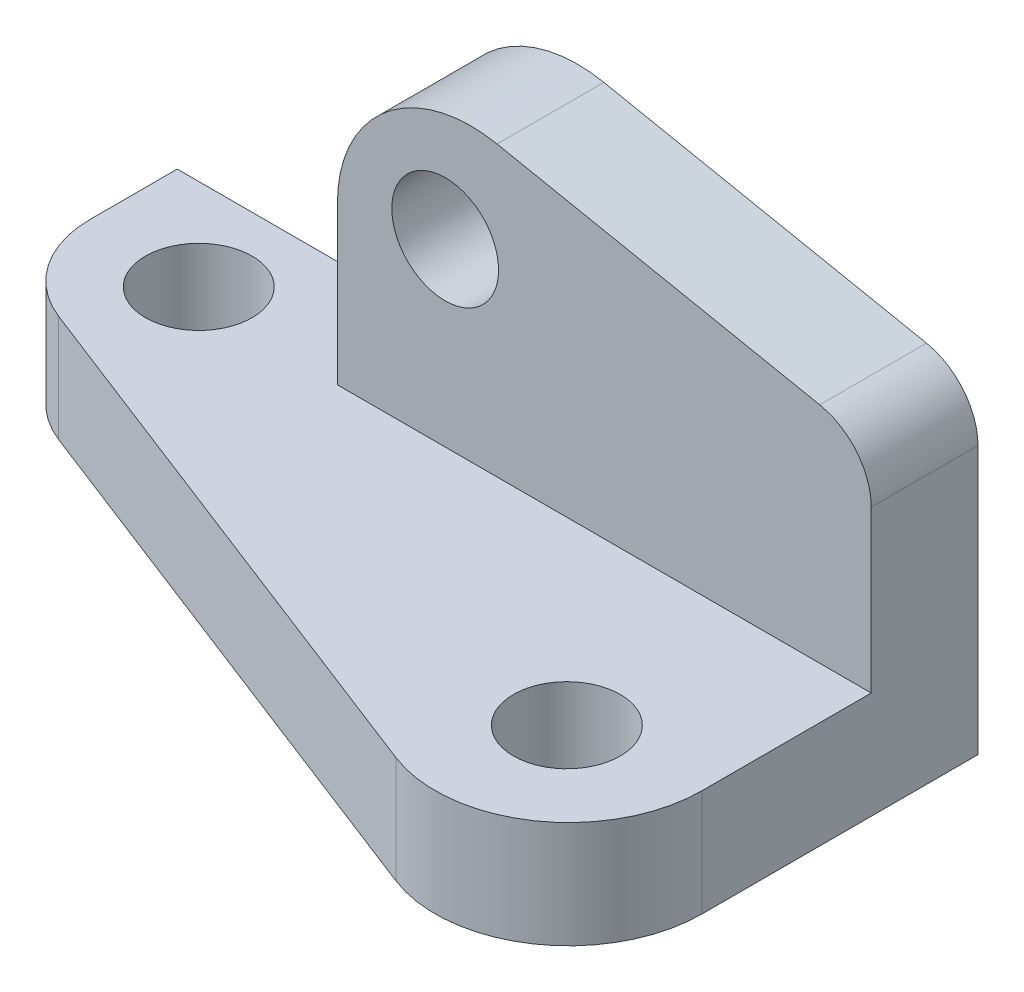
SolidWorks part; units mm, degrees
ref_plane "Front Plane" through (0, 0, 0) normal (0, 0, 1) x (1, 0, 0)
ref_plane "Top Plane" through (0, 0, 0) normal (0, 1, 0) x (1, 0, 0)
ref_plane "Right Plane" through (0, 0, 0) normal (1, 0, 0) x (0, 0, -1)
sketch "Sketch1" plane through (0, 0, 0) normal (0, 1, 0) x (1, 0, 0)
  line L0 (0, 0) -> (150, 0)
  line L1 (0, 0) -> (0, -16.3519)
  line L2 (150, 0) -> (150, -51.6899)
  line L3 (115.9645, -75) -> (12.7716, -35)
  arc A0 (0, -16.3519) -> (12.7716, -35) centre (20, -16.3519) ccw
  arc A1 (150, -51.6899) -> (115.9645, -75) centre (125, -51.6899) cw
  dimension "D1" = 20
  dimension "D2" = 25
  dimension "D3" = 35
  dimension "D4" = 75
  dimension "D5" = 150
extrude "Boss-Extrude1" add sketch "Sketch1" along normal blind 20
sketch "Sketch3" plane through (0, 0, 0) normal (0, 0, 1) x (1, 0, 0)
  line L0 (150, 0) -> (50, 0)
  line L1 (150, 0) -> (0, 0) construction
  line L3 (150, 60) -> (50, 80)
  line L6 (50, 0) -> (50, 80)
  line L7 (150, 0) -> (150, 60)
  dimension "D1" = 60
  dimension "D2" = 100
  dimension "D3" = 80
extrude "Boss-Extrude4" add sketch "Sketch3" along normal blind 20
fillet "Fillet1" radius 25 1 edges at (50, 80, 10)
fillet "Fillet2" radius 12 1 edges at (150, 60, 10)
hole_wizard "Ø20.0mm Dowel Hole2" positions "Sketch10" profile "Sketch11" hole size "Ø20.0" standard "ANSI Metric" end condition through all
sketch "Sketch10" plane through (0, 0, 20) normal (0, 0, 1) x (1, 0, 0)
  point P0 (70.1852, 53.7137)
  point P2 (70.1852, 53.7137)
sketch "Sketch11" plane through (70.1852, 53.7137, 20) normal (1, 0, 0) x (0, -1, 0)
  line L0 (0, 0) -> (0, 20)
  line L1 (0, 20) -> (10, 20)
  line L2 (10, 20) -> (10, 0)
  line L5 (10, 0) -> (0, 0)
  line L11 (0, -6.35) -> (0, 107.95) construction
  dimension "Thru Hole Dia." = 20
  dimension "Thru Hole Depth" = 20
hole_wizard "Ø20.0mm Dowel Hole4" positions "Sketch14" profile "Sketch15" hole size "Ø20.0" standard "ANSI Metric" end condition through all
sketch "Sketch14" plane through (0, 20, 0) normal (0, 1, 0) x (1, 0, 0)
  point P0 (21.1263, -17.1033)
sketch "Sketch15" plane through (21.1263, 20, 17.1033) normal (1, 0, 0) x (0, 0, 1)
  line L0 (0, 0) -> (0, 20)
  line L1 (0, 20) -> (10, 20)
  line L2 (10, 20) -> (10, 0)
  line L5 (10, 0) -> (0, 0)
  line L11 (0, -6.35) -> (0, 107.95) construction
  dimension "Thru Hole Dia." = 20
  dimension "Thru Hole Depth" = 20
hole_wizard "Ø20.0mm Dowel Hole5" positions "Sketch18" profile "Sketch19" hole size "Ø20.0" standard "ANSI Metric" end condition through all
sketch "Sketch18" plane through (0, 20, 0) normal (0, 1, 0) x (1, 0, 0)
  point P0 (126.7188, -53.7375)
sketch "Sketch19" plane through (126.7188, 20, 53.7375) normal (1, 0, 0) x (0, 0, 1)
  line L0 (0, 0) -> (0, 20)
  line L1 (0, 20) -> (10, 20)
  line L2 (10, 20) -> (10, 0)
  line L5 (10, 0) -> (0, 0)
  line L11 (0, -6.35) -> (0, 107.95) construction
  dimension "Thru Hole Dia." = 20
  dimension "Thru Hole Depth" = 20
